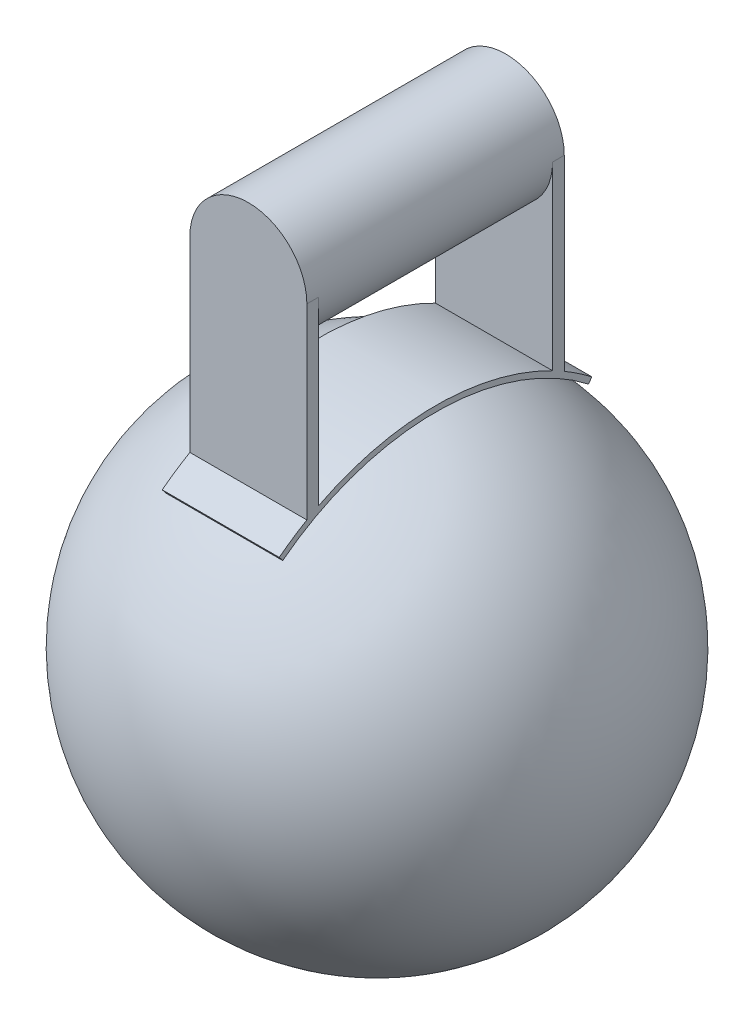
SolidWorks part; units mm, degrees
ref_plane "Front Plane" through (0, 0, 0) normal (0, 0, 1) x (1, 0, 0)
ref_plane "Top Plane" through (0, 0, 0) normal (0, 1, 0) x (1, 0, 0)
ref_plane "Right Plane" through (0, 0, 0) normal (1, 0, 0) x (0, 0, -1)
sketch "Sketch1" plane through (665.831, 953.9862, 1351.7281) normal (0, 0, 1) x (0.9995, 0.0313, 0)
  circle A0 centre (-108.7438, -120.1834) radius 5 construction
  circle A1 centre (-108.7438, -120.1834) radius 5
extrude "Boss-Extrude1" add sketch "Sketch1" along normal blind 20
sketch "Sketch2" plane through (0, 0, 1371.7281) normal (0, 0, 1) x (1, 0, 0)
  line L1 (555.9057, 830.455) -> (565.9057, 830.455)
  line L2 (555.9057, 830.455) -> (555.9057, 814.4626)
  line L3 (555.9057, 814.4626) -> (565.9057, 814.4626)
  line L4 (565.9057, 830.455) -> (565.9057, 814.4626)
  circle A0 centre (560.9057, 830.455) radius 5
  circle M1 centre (560.9057, 830.455) radius 5
extrude "Boss-Extrude2" add sketch "Sketch2" along normal blind 1 contours L1 M1 | L1 M1 | L4 L2 L3 M1
ref_plane "Plane1" through (665.831, 953.9862, 1361.7281) normal (0, 0, 1) x (0.9995, 0.0313, 0)
mirror "Mirror1" about plane through (665.831, 953.9862, 1361.7281) normal (0, 0, 1) of "Boss-Extrude2"
sketch "Sketch3" plane through (555.9057, 0, 0) normal (-1, 0, 0) x (0, 0, 1)
  line L0 (1361.7281, 863.8733) -> (1361.7281, 1044.0991) construction
  line L1 (1348.3673, 812.8757) -> (1348.6637, 812.4914)
  line L2 (1361.9888, 817.6787) -> (1361.9888, 817.1579)
  line L3 (1375.0888, 812.8757) -> (1374.7925, 812.4914)
  arc A0 (1375.0888, 812.8757) -> (1348.3673, 812.8757) centre (1361.7281, 795.5485) ccw
  arc A1 (1374.7925, 812.4914) -> (1348.6637, 812.4914) centre (1361.7281, 795.5485) ccw
  line M5 (1351.7281, 814.4626) -> (1351.7281, 830.455)
extrude "Boss-Extrude3" add sketch "Sketch3" against normal blind 10 contours A1 L3 A0 L2 | A1 L2 A0 M5
sketch "Sketch4" plane through (406.565, 879.9344, 1361.7281) normal (0, 0, 1) x (1, 0, 0)
  line L0 (154.3407, -62.8846) -> (154.3407, -102.8846)
  line L1 (149.3407, -65.4719) -> (159.3407, -65.4719) construction
  line L2 (149.3407, -65.4719) -> (159.3407, -65.4719) construction
  line L3 (159.3407, -64.9246) -> (159.3407, -62.5058) construction
  line L4 (159.3407, -64.9246) -> (159.3407, -62.5058) construction
  arc A0 (154.3407, -102.8846) -> (154.3407, -62.8846) centre (154.3407, -82.8846) ccw
  point P5 (-139.1009, -106.4357)
  point P6 (154.3407, -84.4007)
  point P7 (154.3407, -82.8846)
  point P10 (154.3407, -65.4719)
  point P11 (0, 0)
  dimension "D1" = 20
revolve "Revolve1" add sketch "Sketch4" angle 360 about L0
